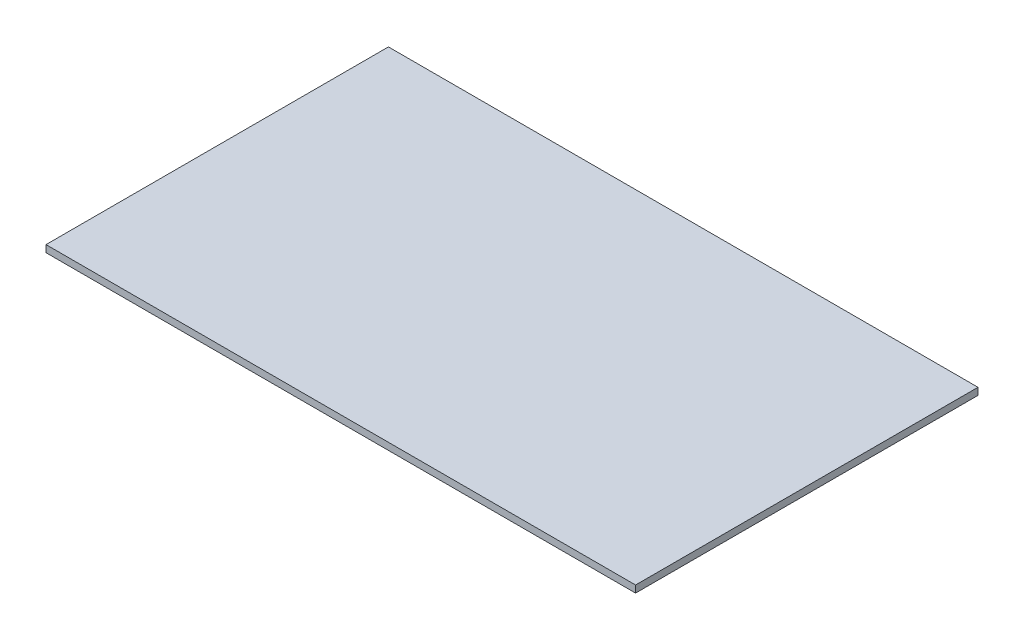
SolidWorks part; units mm, degrees
ref_plane "Front Plane" through (0, 0, 0) normal (0, 0, 1) x (1, 0, 0)
ref_plane "Top Plane" through (0, 0, 0) normal (0, 1, 0) x (1, 0, 0)
ref_plane "Right Plane" through (0, 0, 0) normal (1, 0, 0) x (0, 0, -1)
sketch "Sketch1" plane through (0, 0, 0) normal (0, 1, 0) x (1, 0, 0)
  line L1 (0, 0) -> (50.292, 0)
  line L2 (0, 0) -> (0, 29.21)
  line L3 (0, 29.21) -> (50.292, 29.21)
  line L4 (50.292, 0) -> (50.292, 29.21)
  dimension "D1" = 29.21
  dimension "D2" = 50.292
extrude "Boss-Extrude1" add sketch "Sketch1" along normal blind 0.6
